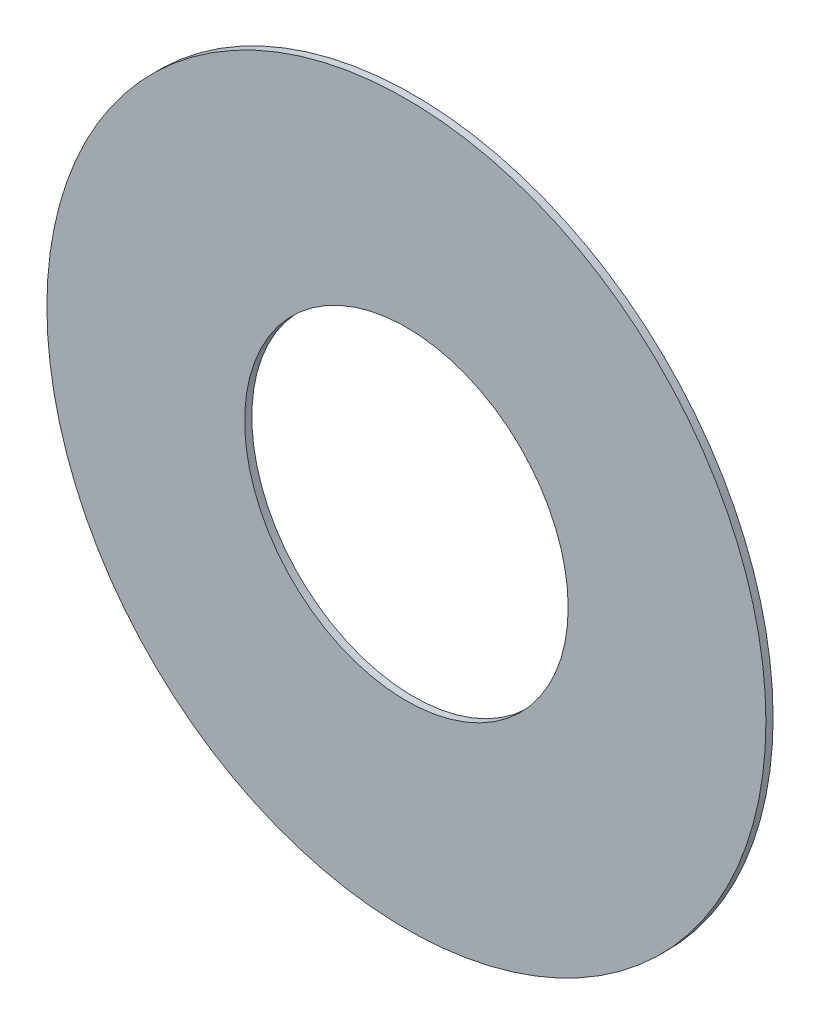
SolidWorks part; units mm, degrees
ref_plane "Plan de face" through (0, 0, 0) normal (0, 0, 1) x (1, 0, 0)
ref_plane "Plan de dessus" through (0, 0, 0) normal (0, 1, 0) x (1, 0, 0)
ref_plane "Plan de droite" through (0, 0, 0) normal (1, 0, 0) x (0, 0, -1)
sketch "Esquisse1" plane through (0, 0, 0) normal (0, 0, 1) x (1, 0, 0)
  circle A0 centre (0, 0) radius 12
  dimension "D1" = 24
extrude "Boss.-Extru.1" add sketch "Esquisse1" along normal blind 0.24
sketch "Esquisse2" plane through (0, 0, 0) normal (0, 0, 1) x (1, 0, 0)
  circle A0 centre (0, 0) radius 5.4
  dimension "D1" = 10.8
extrude "Enlèv. mat.-Extru.1" cut sketch "Esquisse2" along normal blind 44
